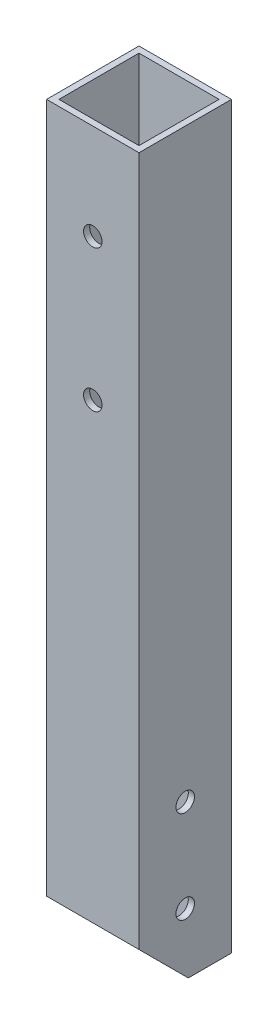
SolidWorks part; units mm, degrees
material "6063-T6"
ref_plane "前视基准面" through (0, 0, 0) normal (0, 0, 1) x (1, 0, 0)
ref_plane "上视基准面" through (0, 0, 0) normal (0, 1, 0) x (1, 0, 0)
ref_plane "右视基准面" through (0, 0, 0) normal (1, 0, 0) x (0, 0, -1)
sketch "草图1" plane through (0, 0, 0) normal (0, 1, 0) x (1, 0, 0)
  line B0 (-6.5, 6.5) -> (6.5, 6.5)
  line B1 (-7.5, -7.5) -> (7.5, -7.5)
  line B2 (-7.5, -7.5) -> (-7.5, 7.5)
  line B3 (-7.5, 7.5) -> (7.5, 7.5)
  line B4 (7.5, -7.5) -> (7.5, 7.5)
  line B5 (6.5, -6.5) -> (6.5, 6.5)
  line B6 (-6.5, -6.5) -> (6.5, -6.5)
  line B7 (-6.5, -6.5) -> (-6.5, 6.5)
sketch_block_instance "块-15X15X1-1"
sketch_block "块-15X15X1" parameters "D1"=15
extrude "凸台-拉伸1" add sketch "草图1" along normal blind 120
sketch "草图2" plane through (0, 0, 7.5) normal (0, 0, 1) x (1, 0, 0)
  line L0 (0, 120) -> (0, 0) construction
  line L1 (-7.5, 120) -> (7.5, 120) construction
  circle A0 centre (0, 104.5) radius 1.5
  circle A1 centre (0, 81.5) radius 1.5
  dimension "D1" = 3
  dimension "D2" = 23
  dimension "D3" = 15.5
extrude "切除-拉伸1" cut sketch "草图2" against normal through all
sketch "草图3" plane through (-7.5, 0, 0) normal (-1, 0, 0) x (0, 0, 1)
  line L0 (0, 120) -> (0, 0) construction
  line L1 (-7.5, 120) -> (7.5, 120) construction
  line L2 (-7.5, 0) -> (7.5, 0) construction
  line L3 (-0.5, 0) -> (7.5, 0)
  line L4 (7.5, 0) -> (7.5, 8)
  line L5 (7.5, 120) -> (7.5, 0) construction
  line L6 (7.5, 8) -> (-0.5, 0)
  circle A0 centre (0, 10) radius 1.5
  circle A1 centre (0, 25) radius 1.5
  dimension "D1" = 15
  dimension "D2" = 3
  dimension "D3" = 10
  dimension "D4" = 45
  dimension "D5" = 8
extrude "切除-拉伸2" cut sketch "草图3" against normal through all
